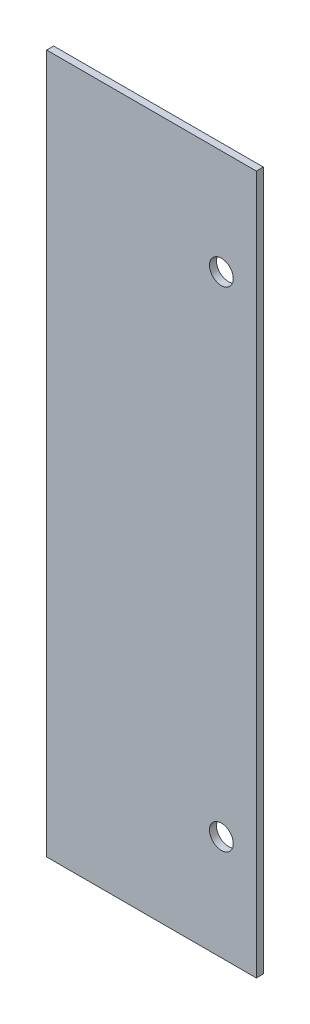
SolidWorks part; units mm, degrees
ref_plane "Front Plane" through (0, 0, 0) normal (0, 0, 1) x (1, 0, 0)
ref_plane "Top Plane" through (0, 0, 0) normal (0, 1, 0) x (1, 0, 0)
ref_plane "Right Plane" through (0, 0, 0) normal (1, 0, 0) x (0, 0, -1)
sketch "Sketch1" plane through (0, 0, 0) normal (0, 0, 1) x (1, 0, 0)
  line L1 (-15, -50) -> (15, -50)
  line L2 (-15, -50) -> (-15, 50)
  line L3 (-15, 50) -> (15, 50)
  line L4 (15, -50) -> (15, 50)
  line L5 (-15, -50) -> (15, 50) construction
  line L6 (-15, 50) -> (15, -50) construction
  point P0 (0, 0)
extrude "Boss-Extrude1" add sketch "Sketch1" against normal blind 1
sketch "Sketch2" plane through (0, 0, 0) normal (0, 0, 1) x (1, 0, 0)
  circle A0 centre (10, -35) radius 1.7
  circle A1 centre (10, 35) radius 1.7
extrude "Cut-Extrude1" cut sketch "Sketch2" along normal through all and the other way through all
